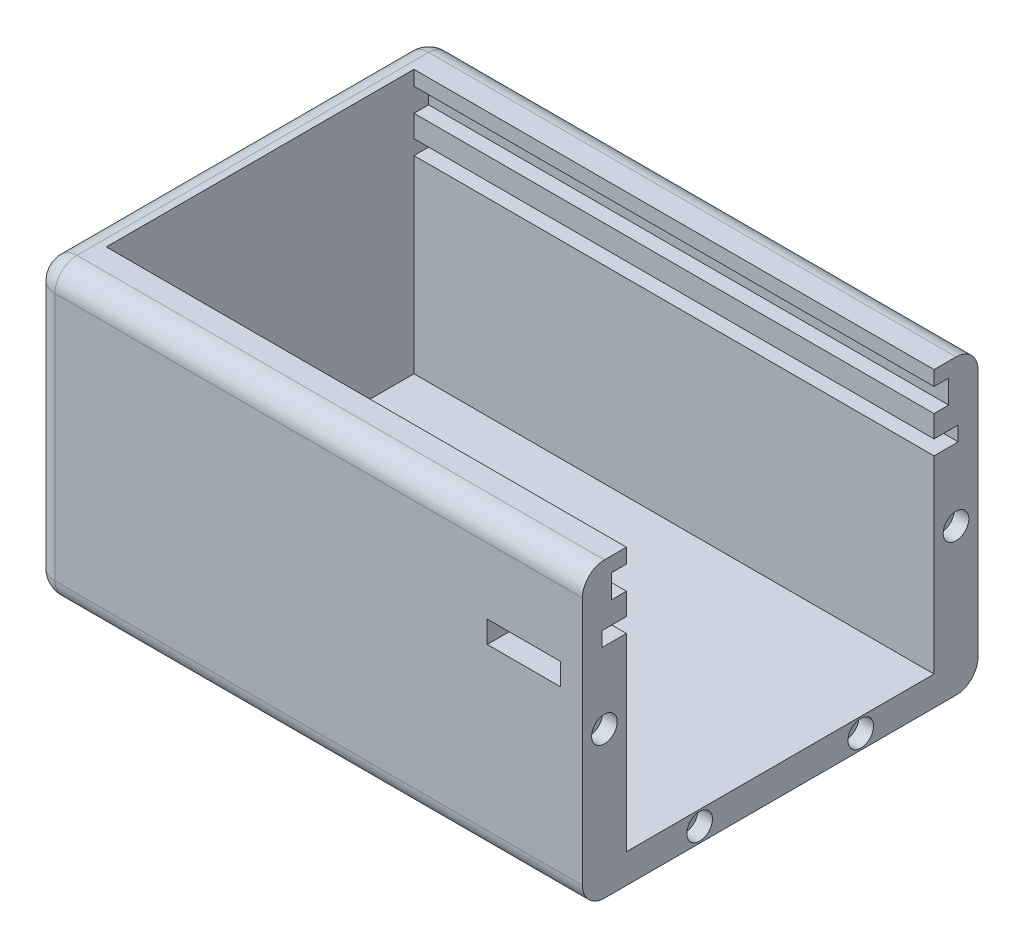
SolidWorks part; units mm, degrees
ref_plane "Plan de face" through (0, 0, 0) normal (0, 0, 1) x (1, 0, 0)
ref_plane "Plan de dessus" through (0, 0, 0) normal (0, 1, 0) x (1, 0, 0)
ref_plane "Plan de droite" through (0, 0, 0) normal (1, 0, 0) x (0, 0, -1)
sketch "Esquisse1" plane through (0, 0, 0) normal (0, 1, 0) x (1, 0, 0)
  line L1 (-37.5, 27) -> (37.5, 27)
  line L2 (-37.5, 27) -> (-37.5, -27)
  line L3 (-37.5, -27) -> (37.5, -27)
  line L4 (37.5, 27) -> (37.5, -27)
  line L5 (-37.5, 27) -> (37.5, -27) construction
  line L6 (-37.5, -27) -> (37.5, 27) construction
  point P0 (0, 0)
  dimension "D1" = 75
  dimension "D2" = 54
extrude "Boss.-Extru.1" add sketch "Esquisse1" along normal blind 40
sketch "Esquisse2" plane through (37.5, 0, 0) normal (1, 0, 0) x (0, 0, -1)
  line L0 (27, 0) -> (-27, 0) construction
  line L1 (-21, 40.2303) -> (21, 40.2303)
  line L2 (-21, 40.2303) -> (-21, 4)
  line L3 (-21, 4) -> (21, 4)
  line L4 (21, 40.2303) -> (21, 4)
  line L5 (-21, 40.2303) -> (21, 4) construction
  line L6 (-21, 4) -> (21, 40.2303) construction
  line L7 (-27, 40) -> (27, 40) construction
  line L8 (27, 40) -> (27, 0) construction
  point P0 (0, 22.1151)
  dimension "D1" = 4
  dimension "D2" = 0.2303
  dimension "D3" = 6
  dimension "D4" = 42
extrude "Enlèv. mat.-Extru.1" cut sketch "Esquisse2" against normal blind 71
sketch "Esquisse4" plane through (-33.5, 0, 0) normal (1, 0, 0) x (0, 0, -1)
  line L0 (-21, 40) -> (-21, 38)
  line L1 (-21, 40) -> (-21, 4) construction
  line L2 (21, 4) -> (21, 40) construction
  line L4 (-21, 38) -> (-21, 34.8)
  line L6 (21, 38) -> (21, 34.8)
  line L7 (-21, 34.8) -> (-21, 31.8)
  line L8 (-21, 38) -> (-23, 38)
  line L9 (-21, 38) -> (-21, 34.8)
  line L10 (-21, 34.8) -> (-23, 34.8)
  line L11 (-23, 38) -> (-23, 34.8)
  line L12 (21, 38) -> (23, 38)
  line L13 (21, 38) -> (21, 34.8)
  line L14 (21, 34.8) -> (23, 34.8)
  line L15 (23, 38) -> (23, 34.8)
  line L16 (21, 4) -> (21, 40) construction
  line L18 (-21, 31.8) -> (-21, 29.8)
  line L20 (21, 31.8) -> (21, 29.8)
  line L21 (21, 40) -> (27, 40) construction
  line L22 (-21, 31.8) -> (-24.3, 31.8)
  line L23 (-21, 31.8) -> (-21, 29.8)
  line L24 (-21, 29.8) -> (-24.3, 29.8)
  line L25 (-24.3, 31.8) -> (-24.3, 29.8)
  line L26 (21, 31.8) -> (24.3, 31.8)
  line L27 (21, 31.8) -> (21, 29.8)
  line L28 (21, 29.8) -> (24.3, 29.8)
  line L29 (24.3, 31.8) -> (24.3, 29.8)
  line M15 (21, 4) -> (21, 40)
  line M17 (-21, 40) -> (-21, 4)
  dimension "D1" = 2
  dimension "D2" = 3.2
  dimension "D3" = 2
  dimension "D4" = 2
  dimension "D5" = 3
  dimension "D6" = 2
  dimension "D7" = 3.3
  dimension "D8" = 3.3
  dimension "D9" = 2
  dimension "D10" = 3
  dimension "D11" = 3.2
  dimension "D12" = 2
extrude "Enlèv. mat.-Extru.2" cut sketch "Esquisse4" along normal blind 72 contours L8 L11 L10 M17 | L22 L25 L24 M17 | L15 L12 L14 M15 | L29 L26 L28 M15
sketch "Esquisse8" plane through (0, 0, 27) normal (0, 0, 1) x (1, 0, 0)
  line L0 (-37.5, 0) -> (37.5, 0) construction
  line L1 (34.5, 28) -> (24.5, 28)
  line L2 (34.5, 28) -> (34.5, 25)
  line L3 (34.5, 25) -> (24.5, 25)
  line L4 (24.5, 28) -> (24.5, 25)
  line L5 (37.5, 40) -> (37.5, 0) construction
  dimension "D1" = 25
  dimension "D2" = 3
  dimension "D3" = 10
  dimension "D4" = 3
extrude "Enlèv. mat.-Extru.5" cut sketch "Esquisse8" against normal blind 11
sketch "Esquisse9" plane through (37.5, 0, 0) normal (1, 0, 0) x (0, 0, -1)
  line L0 (-27, 40) -> (-27, 0) construction
  line L1 (27, 40) -> (27, 0) construction
  line L2 (-27, 0) -> (27, 0) construction
  line L4 (27, 0) -> (-27, 0) construction
  line L5 (-27, 0) -> (27, 0) construction
  line L6 (27, 0) -> (-27, 0) construction
  circle A0 centre (-24, 20) radius 1.75
  circle A1 centre (-11, 2) radius 1.75
  circle A2 centre (11, 2) radius 1.75
  circle A3 centre (24, 20) radius 1.75
  dimension "D5" = 3.5
  dimension "D6" = 3.5
  dimension "D7" = 3.5
  dimension "D8" = 3.5
  dimension "D1" = 3
  dimension "D2" = 3
  dimension "D3" = 2
  dimension "D4" = 2
  dimension "D9" = 20
  dimension "D10" = 20
  dimension "D11" = 16
  dimension "D12" = 16
extrude "Enlèv. mat.-Extru.6" cut sketch "Esquisse9" against normal blind 2
fillet "Congé1" radius 3 8 edges at (0, 0, -27) (0, 0, 27) (-37.5, 0, 0) (-37.5, 20, 27) (-37.5, 20, -27) (0, 40, 27) (-37.5, 40, 0) (0, 40, -27)
